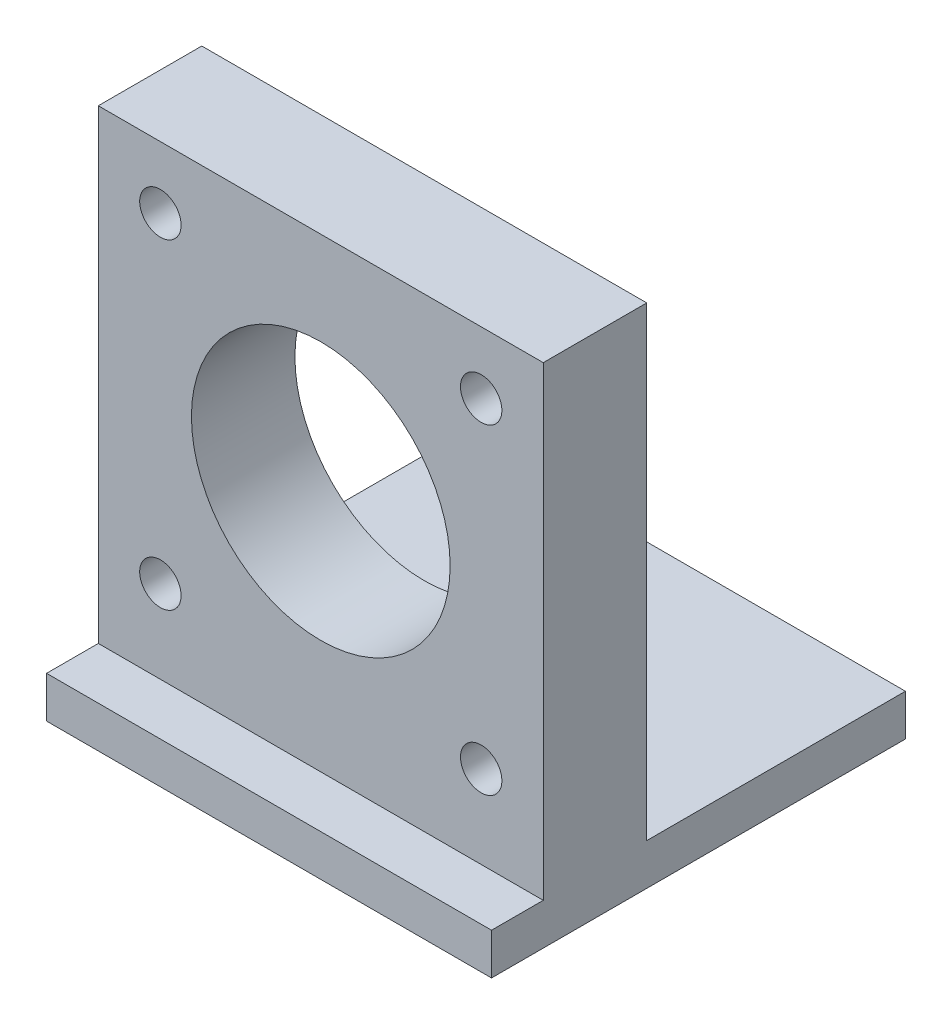
SolidWorks part; units mm, degrees
ref_plane "Front Plane" through (0, 0, 0) normal (0, 0, 1) x (1, 0, 0)
ref_plane "Top Plane" through (0, 0, 0) normal (0, 1, 0) x (1, 0, 0)
ref_plane "Right Plane" through (0, 0, 0) normal (1, 0, 0) x (0, 0, -1)
sketch "Sketch1" plane through (0, 0, 0) normal (0, 1, 0) x (1, 0, 0)
  line L1 (-27.0906, -14.3306) -> (15.9094, -14.3306)
  line L2 (-27.0906, -14.3306) -> (-27.0906, 25.6694)
  line L3 (-27.0906, 25.6694) -> (15.9094, 25.6694)
  line L4 (15.9094, -14.3306) -> (15.9094, 25.6694)
  dimension "D1" = 40
  dimension "D2" = 43
extrude "Boss-Extrude1" add sketch "Sketch1" along normal blind 4
sketch "Sketch2" plane through (0, 4, 0) normal (0, 1, 0) x (1, 0, 0)
  line L0 (-27.0906, 25.6694) -> (-27.0906, -14.3306) construction
  line L1 (-27.0906, 0.6694) -> (15.9094, 0.6694)
  line L2 (-27.0906, 0.6694) -> (-27.0906, -9.3306)
  line L3 (-27.0906, -9.3306) -> (15.9094, -9.3306)
  line L4 (15.9094, 0.6694) -> (15.9094, -9.3306)
  line L5 (15.9094, -14.3306) -> (15.9094, 25.6694) construction
  line L6 (-27.0906, -14.3306) -> (15.9094, -14.3306) construction
  dimension "D1" = 5
  dimension "D2" = 10
extrude "Boss-Extrude2" add sketch "Sketch2" along normal blind 45
sketch "Sketch3" plane through (0, 0, 9.3306) normal (0, 0, 1) x (1, 0, 0)
  line L0 (-27.0906, 49) -> (-27.0906, 4) construction
  line L1 (15.9094, 49) -> (15.9094, 4) construction
  line L2 (-27.0906, 4) -> (15.9094, 4) construction
  line L3 (-27.0906, 49) -> (15.9094, 49) construction
  circle A0 centre (-5.5906, 27.5) radius 12.5
  circle A1 centre (-21.0906, 43) radius 2
  circle A2 centre (9.9094, 43) radius 2
  circle A3 centre (9.9094, 12) radius 2
  circle A4 centre (-21.0906, 12) radius 2
  dimension "D7" = 4
  dimension "D8" = 4
  dimension "D10" = 4
  dimension "D12" = 4
  dimension "D13" = 25
  dimension "D1" = 21.5
  dimension "D2" = 21.5
  dimension "D3" = 23.5
  dimension "D4" = 21.5
  dimension "D5" = 15.5
  dimension "D6" = 15.5
  dimension "D9" = 15.5
  dimension "D11" = 15.5
extrude "Cut-Extrude1" cut sketch "Sketch3" against normal up to next
